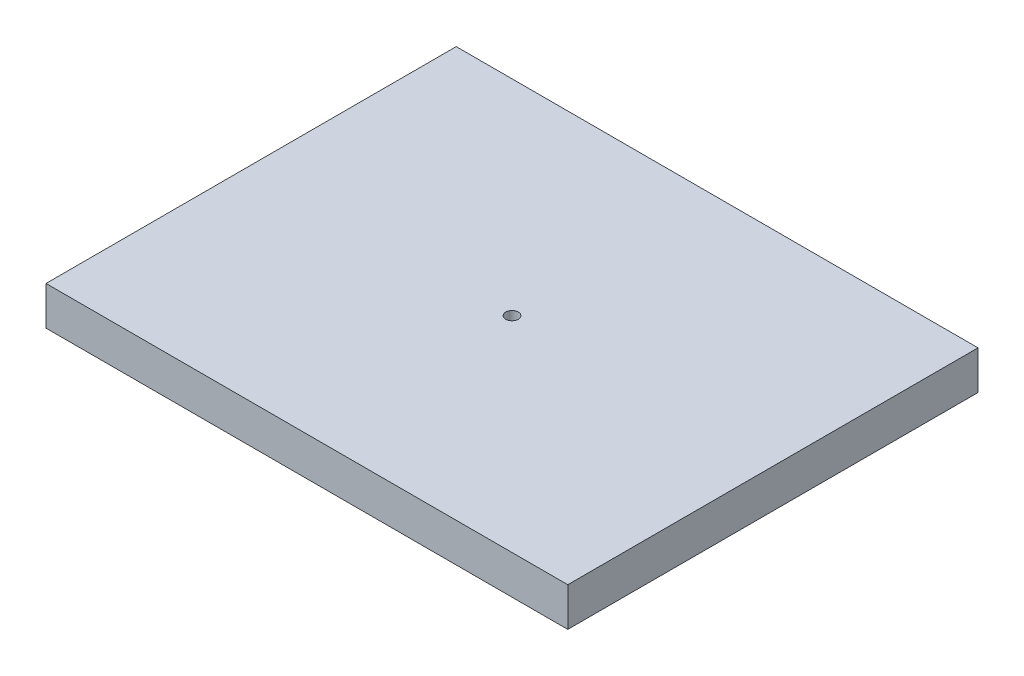
SolidWorks part; units mm, degrees
ref_plane "Front Plane" through (0, 0, 0) normal (0, 0, 1) x (1, 0, 0)
ref_plane "Top Plane" through (0, 0, 0) normal (0, 1, 0) x (1, 0, 0)
ref_plane "Right Plane" through (0, 0, 0) normal (1, 0, 0) x (0, 0, -1)
sketch "Sketch1" plane through (0, 0, 0) normal (0, 1, 0) x (1, 0, 0)
  line L1 (-68.4544, -53.821) -> (68.4544, -53.821)
  line L2 (-68.4544, -53.821) -> (-68.4544, 53.821)
  line L3 (-68.4544, 53.821) -> (68.4544, 53.821)
  line L4 (68.4544, -53.821) -> (68.4544, 53.821)
  line L5 (-68.4544, -53.821) -> (68.4544, 53.821) construction
  line L6 (-68.4544, 53.821) -> (68.4544, -53.821) construction
  point P0 (0, 0)
extrude "Boss-Extrude1" add sketch "Sketch1" along normal blind 10.16
hole_wizard "Tap Drill for M4x0.7 Tap1" positions "Sketch2" profile "Sketch3" hole size "M4x0.7" standard "ANSI Metric" end condition through all
sketch "Sketch2" plane through (0, 10.16, 0) normal (0, 1, 0) x (1, 0, 0)
  point P0 (0, 0)
sketch "Sketch3" plane through (0, 10.16, 0) normal (1, 0, 0) x (0, 0, 1)
  line L0 (0, 0) -> (0, 10.16)
  line L1 (0, 10.16) -> (1.65, 10.16)
  line L2 (1.65, 10.16) -> (1.65, 0)
  line L5 (1.65, 0) -> (0, 0)
  line L11 (0, -6.35) -> (0, 107.95) construction
  dimension "Thru Hole Dia." = 3.3
  dimension "Thru Hole Depth" = 10.16
